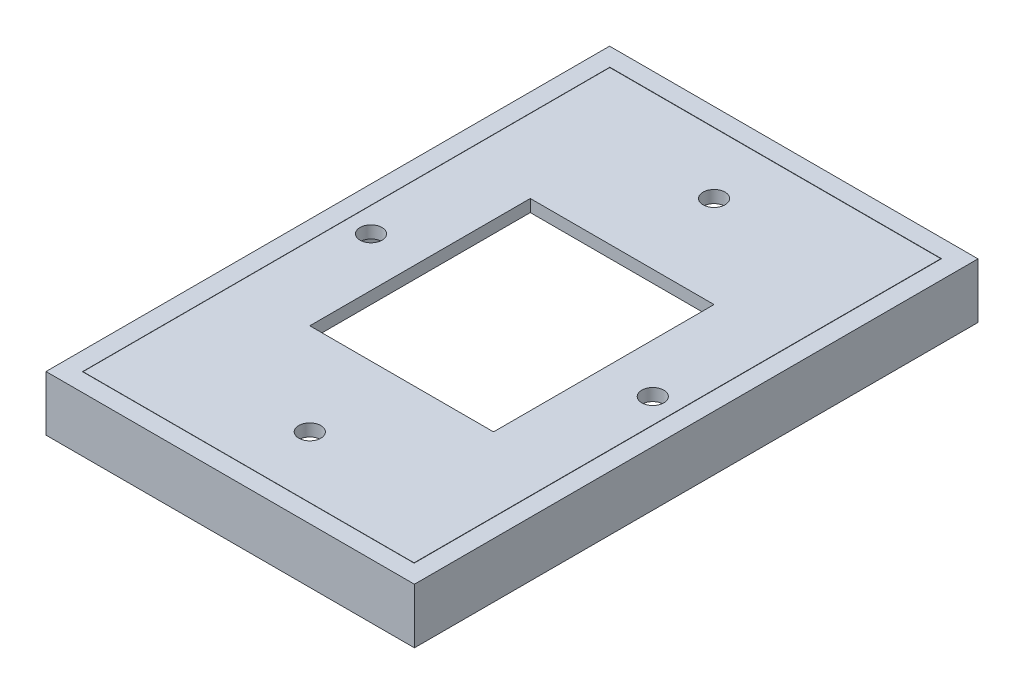
SolidWorks part; units mm, degrees
ref_plane "Front Plane" through (0, 0, 0) normal (0, 0, 1) x (1, 0, 0)
ref_plane "Top Plane" through (0, 0, 0) normal (0, 1, 0) x (1, 0, 0)
ref_plane "Right Plane" through (0, 0, 0) normal (1, 0, 0) x (0, 0, -1)
sketch "Sketch1" plane through (0, 0, 0) normal (0, 1, 0) x (1, 0, 0)
  line L1 (-15, -18) -> (15, -18)
  line L2 (-15, -18) -> (-15, 18)
  line L3 (-15, 18) -> (15, 18)
  line L4 (15, -18) -> (15, 18)
  line L5 (-15, -18) -> (15, 18) construction
  line L6 (-15, 18) -> (15, -18) construction
  line L7 (27.025, -43) -> (-27.025, -43)
  line L8 (27.025, -43) -> (27.025, 43)
  line L9 (27.025, 43) -> (-27.025, 43)
  line L10 (-27.025, -43) -> (-27.025, 43)
  line L11 (27.025, -43) -> (-27.025, 43) construction
  line L12 (27.025, 43) -> (-27.025, -43) construction
  point P0 (0, 0)
  point P6 (0, 0)
  dimension "D1" = 30
  dimension "D2" = 36
  dimension "D3" = 86
  dimension "D4" = 54.05
extrude "Boss-Extrude1" add sketch "Sketch1" along normal blind 2 contours L10 L7 L8 L9 L4 L1 L2 L3
sketch "Sketch2" plane through (0, 0, 0) normal (0, -1, 0) x (1, 0, 0)
  line L0 (27.025, 43) -> (-27.025, 43) construction
  line L1 (27.0827, -43.0555) -> (-27.0677, -43.0555)
  line L2 (27.0827, -43.0555) -> (27.0827, 43.0445)
  line L3 (27.0827, 43.0445) -> (-27.0677, 43.0445)
  line L4 (-27.0677, -43.0555) -> (-27.0677, 43.0445)
  line L5 (27.0827, -43.0555) -> (-27.0677, 43.0445) construction
  line L6 (27.0827, 43.0445) -> (-27.0677, -43.0555) construction
  line L7 (30.0827, -46.0111) -> (-30.0677, -46.0111)
  line L8 (30.0827, -46.0111) -> (30.0827, 46)
  line L9 (30.0827, 46) -> (-30.0677, 46)
  line L10 (-30.0677, -46.0111) -> (-30.0677, 46)
  line L11 (30.0827, -46.0111) -> (-30.0677, 46) construction
  line L12 (30.0827, 46) -> (-30.0677, -46.0111) construction
  point P0 (0.0075, -0.0055)
  point P8 (0.0075, -0.0055)
  point P14 (-27.025, -43)
  point P16 (0, 0)
  point P17 (0, 0)
  point P18 (0, 0)
  dimension "D1" = 3
  dimension "D2" = 3
  dimension "D3" = 86.1
  dimension "D4" = 54.1505
extrude "Boss-Extrude2" add sketch "Sketch2" along normal blind 7 and the other way blind 2
sketch "Sketch3" plane through (0, 2, 0) normal (0, 1, 0) x (1, 0, 0)
  line L0 (-15, -18) -> (-15, 18) construction
  line L1 (-15, 0) -> (-23, 0) construction
  line L2 (0, -18) -> (0, -33) construction
  line L3 (-15, -18) -> (15, -18) construction
  circle A0 centre (0, -33) radius 1.8
  circle A1 centre (-23, 0) radius 1.8
  circle A2 centre (0, 33) radius 1.8
  circle A3 centre (23, 0) radius 1.8
  dimension "D2" = 8
  dimension "D1" = 15
extrude "Cut-Extrude1" cut sketch "Sketch3" against normal blind 2
